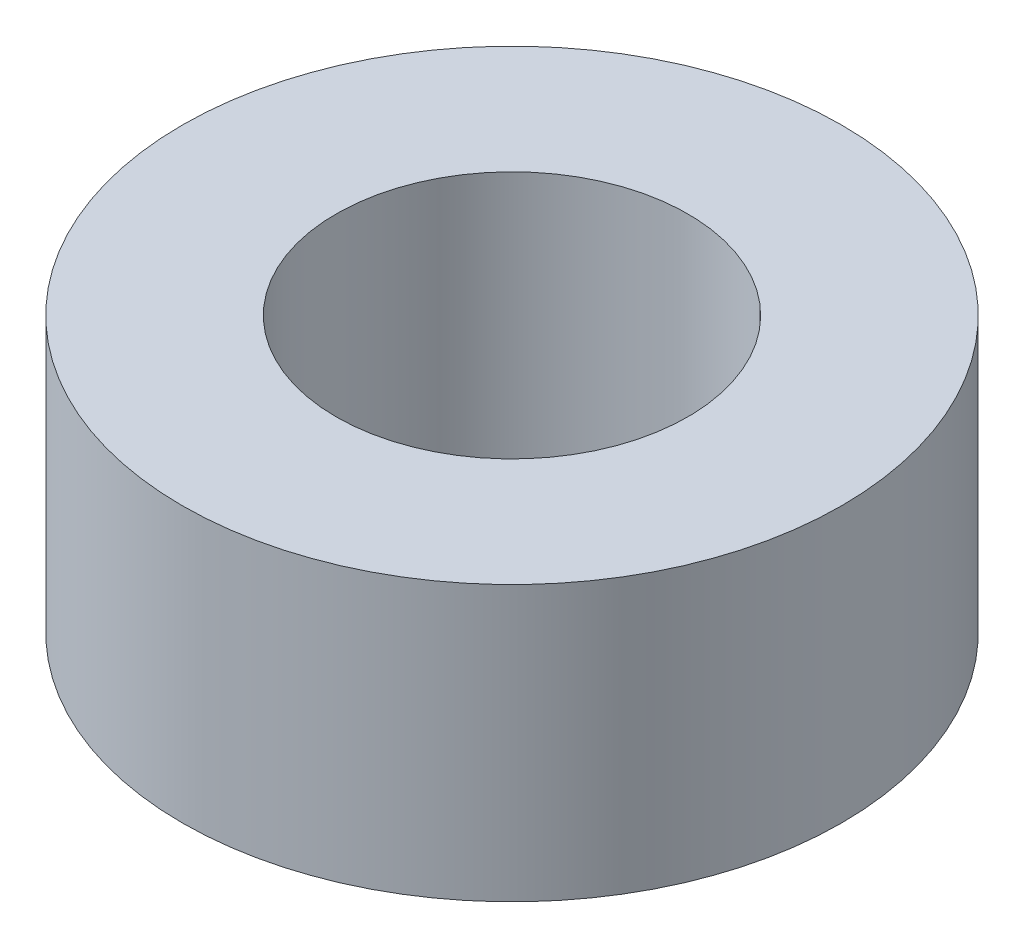
SolidWorks part; units mm, degrees
ref_plane "Front Plane" through (0, 0, 0) normal (0, 0, 1) x (1, 0, 0)
ref_plane "Top Plane" through (0, 0, 0) normal (0, 1, 0) x (1, 0, 0)
ref_plane "Right Plane" through (0, 0, 0) normal (1, 0, 0) x (0, 0, -1)
sketch "Sketch1" plane through (0, 0, 0) normal (0, 1, 0) x (1, 0, 0)
  circle A0 centre (0, 0) radius 1.6
  circle A1 centre (0, 0) radius 3
  dimension "D1" = 3.2
  dimension "D2" = 6
extrude "Boss-Extrude1" add sketch "Sketch1" along normal blind 2.5
